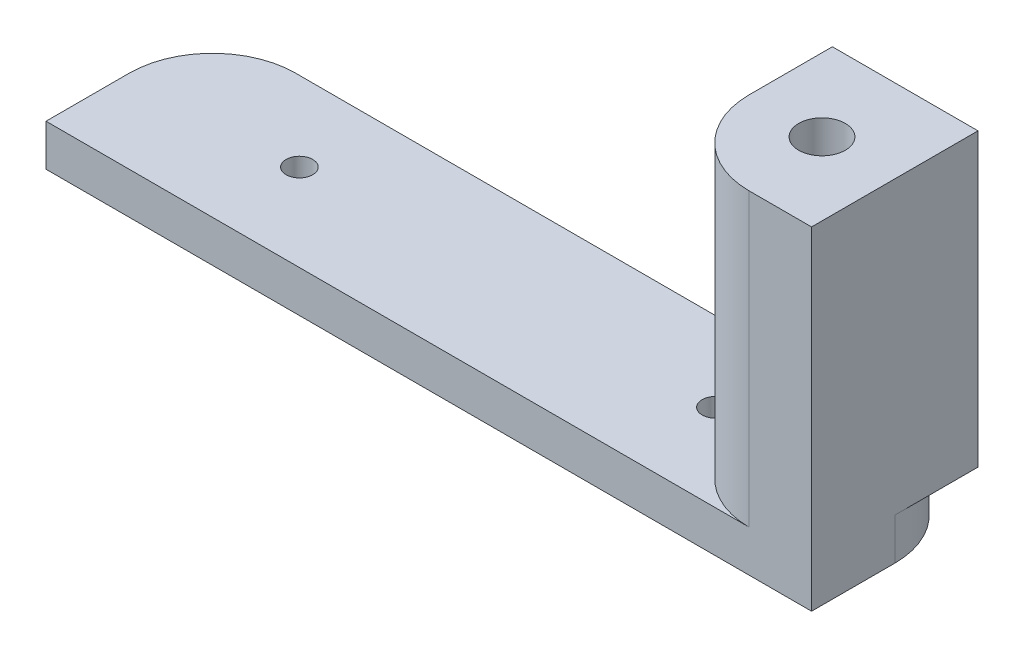
SolidWorks part; units mm, degrees
ref_plane "Front Plane" through (0, 0, 0) normal (0, 0, 1) x (1, 0, 0)
ref_plane "Top Plane" through (0, 0, 0) normal (0, 1, 0) x (1, 0, 0)
ref_plane "Right Plane" through (0, 0, 0) normal (1, 0, 0) x (0, 0, -1)
sketch "Sketch1" plane through (0, 0, 0) normal (0, 1, 0) x (1, 0, 0)
  line L1 (-46, -10) -> (46, -10)
  line L2 (-46, -10) -> (-46, 10)
  line L3 (-46, 10) -> (46, 10)
  line L4 (46, -10) -> (46, 10)
  line L5 (-46, -10) -> (46, 10) construction
  line L6 (-46, 10) -> (46, -10) construction
  point P0 (0, 0)
  dimension "D1" = 92
  dimension "D2" = 20
extrude "Boss-Extrude1" add sketch "Sketch1" along normal blind 5
fillet "Fillet1" radius 10 2 edges at (46, 2.5, -10) (-46, 2.5, -10)
sketch "Sketch2" plane through (0, 5, 0) normal (0, 1, 0) x (1, 0, 0)
  line L0 (-46, 0) -> (-46, -10) construction
  line L1 (-46, -10) -> (46, -10) construction
  circle A0 centre (-26, 0.45) radius 1.6
  circle A2 centre (24, 0.45) radius 1.6
  dimension "D1" = 3.2
  dimension "D2" = 3.2
  dimension "D3" = 20
  dimension "D4" = 50
  dimension "D5" = 10.45
extrude "Cut-Extrude1" cut sketch "Sketch2" against normal blind 5
sketch "Sketch3" plane through (0, 5, 0) normal (0, 1, 0) x (1, 0, 0)
  line L0 (36, 10) -> (-36, 10) construction
  line L1 (28.5, 10) -> (46, 10)
  line L2 (28.5, 10) -> (28.5, -10)
  line L3 (28.5, -10) -> (46, -10)
  line L4 (46, 10) -> (46, -10)
  circle A0 centre (24, 0.45) radius 1.6 construction
  dimension "D1" = 4.5
  dimension "D2" = 17.5
extrude "Boss-Extrude2" add sketch "Sketch3" along normal blind 35
sketch "Sketch4" plane through (0, 40, 0) normal (0, 1, 0) x (1, 0, 0)
  circle A0 centre (37.25, 0) radius 2.8
  dimension "D1" = 5.6
extrude "Cut-Extrude2" cut sketch "Sketch4" against normal blind 45
fillet "Fillet5" radius 10 1 edges at (28.5, 22.5, 10)
